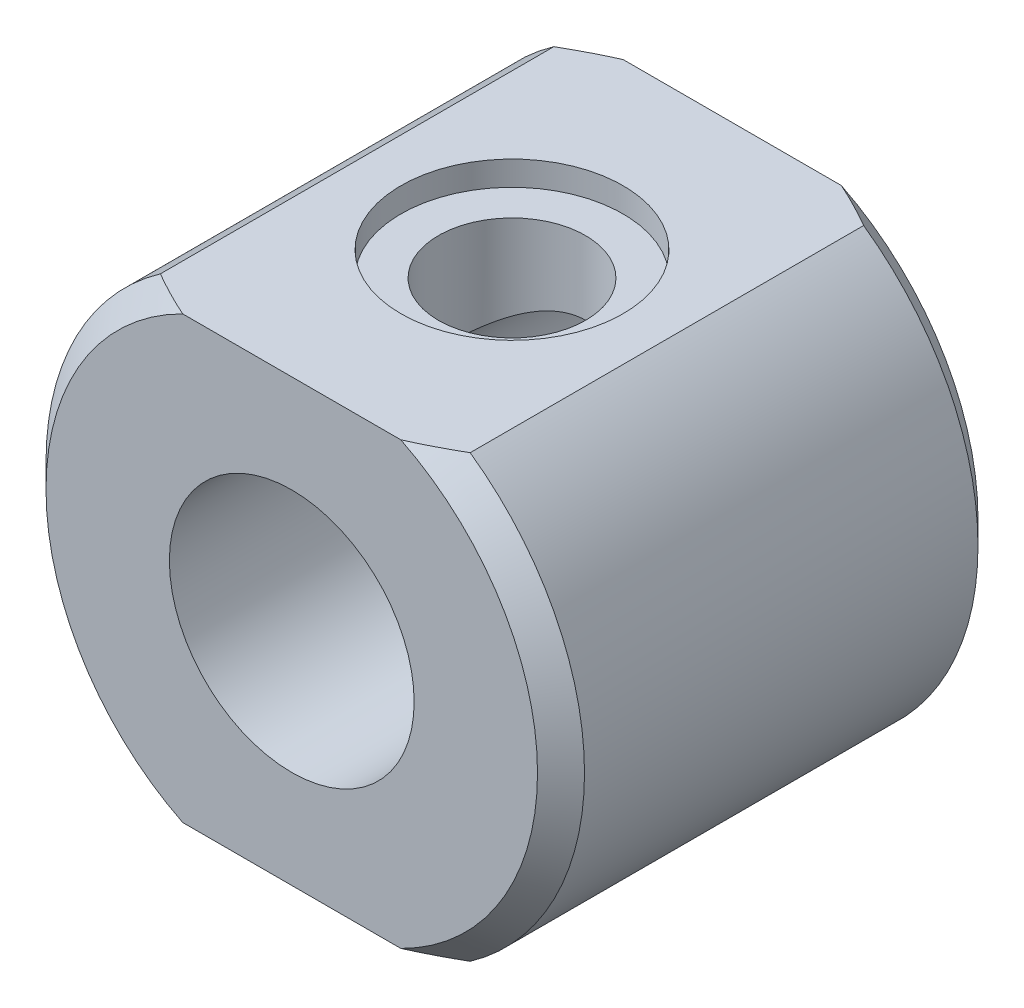
SolidWorks part; units mm, degrees
material "sae 4140"
ref_plane "Front Plane" through (0, 0, 0) normal (0, 0, 1) x (1, 0, 0)
ref_plane "Top Plane" through (0, 0, 0) normal (0, 1, 0) x (1, 0, 0)
ref_plane "Right Plane" through (0, 0, 0) normal (1, 0, 0) x (0, 0, -1)
sketch "Sketch7" plane through (0, 0, 0) normal (0, 0, 1) x (1, 0, 0)
  circle A0 centre (0, 0) radius 17.4625
  dimension "D1" = 34.925
extrude "Boss-Extrude1" add sketch "Sketch7" along normal blind 28.5674
sketch "Sketch9" plane through (0, 0, 28.5674) normal (0, 0, 1) x (1, 0, 0)
  line L1 (-15.875, -14.2837) -> (15.875, -14.2837)
  line L2 (-15.875, -14.2837) -> (-15.875, 14.2837)
  line L3 (-15.875, 14.2837) -> (15.875, 14.2837)
  line L4 (15.875, -14.2837) -> (15.875, 14.2837)
  line L5 (-15.875, -14.2837) -> (15.875, 14.2837) construction
  line L6 (-15.875, 14.2837) -> (15.875, -14.2837) construction
  point P0 (0, 0)
  circle M5 centre (0, 0) radius 17.4625
  dimension "D1" = 28.5674
  dimension "D2" = 31.75
extrude "Cut-Extrude1" cut sketch "Sketch9" against normal blind 28.575 contours L3 M5 | L1 M5
sketch "Sketch10" plane through (0, 14.2837, 0) normal (0, 1, 0) x (1, 0, 0)
  line L0 (-17.4625, -14.2837) -> (10.0457, -14.2837) construction
  line L1 (-17.4625, 0) -> (-17.4625, -28.5674) construction
  line L2 (10.0457, 0) -> (10.0457, -28.5674) construction
  circle A0 centre (0, -14.2837) radius 4.7689
  dimension "D1" = 9.5377
extrude "Cut-Extrude2" cut sketch "Sketch10" against normal through all
sketch "Sketch11" plane through (0, 14.2837, 0) normal (0, 1, 0) x (1, 0, 0)
  circle A0 centre (0, -14.2837) radius 7.2009
  dimension "D1" = 14.4018
extrude "Cut-Extrude3" cut sketch "Sketch11" against normal blind 1.5875
sketch "Sketch12" plane through (0, 0, 28.5674) normal (0, 0, 1) x (1, 0, 0)
  circle A0 centre (0, 0) radius 7.9375
  dimension "D1" = 15.875
extrude "Cut-Extrude4" cut sketch "Sketch12" against normal through all
chamfer "Chamfer2" distance 1.524 distance2 1.524 4 edges at (-17.4625, 0, 0) (17.4625, 0, 0) (-17.4625, 0, 28.5674) (17.4625, 0, 28.5674)
